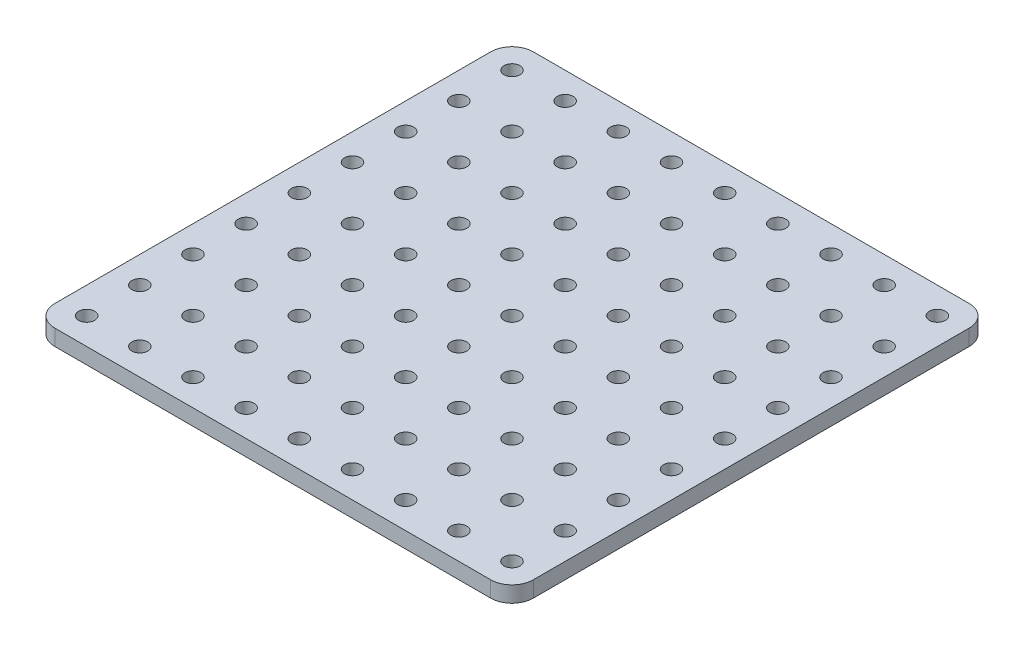
SolidWorks part; units mm, degrees
material "Thornel Mat VMA"
ref_plane "前视基准面" through (0, 0, 0) normal (0, 0, 1) x (1, 0, 0)
ref_plane "上视基准面" through (0, 0, 0) normal (0, 1, 0) x (1, 0, 0)
ref_plane "右视基准面" through (0, 0, 0) normal (1, 0, 0) x (0, 0, -1)
other "Configuration Table"
sketch "草图1" plane through (0, 0, 0) normal (0, 1, 0) x (1, 0, 0)
  line L1 (-45, -45) -> (45, -45)
  line L2 (-45, -45) -> (-45, 45)
  line L3 (-45, 45) -> (45, 45)
  line L4 (45, -45) -> (45, 45)
  line L5 (0, 45) -> (0, -45) construction
  line L6 (-45, 0) -> (45, 0) construction
  point P0 (0, 0)
  dimension "D1" = 90
  dimension "D2" = 90
extrude "凸台-拉伸1" add sketch "草图1" along normal blind 3
sketch "草图2" plane through (0, 3, 0) normal (0, 1, 0) x (1, 0, 0)
  circle A0 centre (-40, 40) radius 1.5
  circle A1 centre (40, 40) radius 1.5
  circle A2 centre (40, -40) radius 1.5
  circle A3 centre (-40, -40) radius 1.5
  point P12 (0, 0)
  dimension "D1" = 40
  dimension "D2" = 40
  dimension "D3" = 3
  dimension "D4" = 4
extrude "切除-拉伸1" cut sketch "草图2" against normal through all
sketch "草图3" plane through (0, 3, 0) normal (0, 1, 0) x (1, 0, 0)
  circle A1 centre (0, 0) radius 1.5
  circle A2 centre (10, 0) radius 1.5
  circle A3 centre (20, 0) radius 1.5
  circle A4 centre (30, 0) radius 1.5
  circle A5 centre (40, 0) radius 1.5
  circle A6 centre (10, 10) radius 1.5
  circle A7 centre (20, 10) radius 1.5
  circle A8 centre (30, 10) radius 1.5
  circle A9 centre (40, 10) radius 1.5
  circle A10 centre (10, 20) radius 1.5
  circle A11 centre (20, 20) radius 1.5
  circle A12 centre (30, 20) radius 1.5
  circle A13 centre (40, 20) radius 1.5
  circle A14 centre (10, 30) radius 1.5
  circle A15 centre (20, 30) radius 1.5
  circle A16 centre (30, 30) radius 1.5
  circle A17 centre (40, 30) radius 1.5
  circle A18 centre (10, 40) radius 1.5
  circle A19 centre (20, 40) radius 1.5
  circle A20 centre (30, 40) radius 1.5
  circle A21 centre (40, 40) radius 1.5
  circle A22 centre (0, 10) radius 1.5
  circle A23 centre (0, 20) radius 1.5
  circle A24 centre (0, 30) radius 1.5
  circle A25 centre (0, 40) radius 1.5
  circle A26 centre (-10, 0) radius 1.5
  circle A27 centre (-20, 0) radius 1.5
  circle A28 centre (-30, 0) radius 1.5
  circle A29 centre (-40, 0) radius 1.5
  circle A30 centre (-10, -10) radius 1.5
  circle A31 centre (-20, -10) radius 1.5
  circle A32 centre (-30, -10) radius 1.5
  circle A33 centre (-40, -10) radius 1.5
  circle A34 centre (-10, -20) radius 1.5
  circle A35 centre (-20, -20) radius 1.5
  circle A36 centre (-30, -20) radius 1.5
  circle A37 centre (-40, -20) radius 1.5
  circle A38 centre (-10, -30) radius 1.5
  circle A39 centre (-20, -30) radius 1.5
  circle A40 centre (-30, -30) radius 1.5
  circle A41 centre (-40, -30) radius 1.5
  circle A42 centre (-10, -40) radius 1.5
  circle A43 centre (-20, -40) radius 1.5
  circle A44 centre (-30, -40) radius 1.5
  circle A45 centre (-40, -40) radius 1.5
  circle A46 centre (0, -10) radius 1.5
  circle A47 centre (0, -20) radius 1.5
  circle A48 centre (0, -30) radius 1.5
  circle A49 centre (0, -40) radius 1.5
  dimension "D1" = 3
  dimension "D2" = 5
  dimension "D3" = 5
  dimension "D4" = 5
  dimension "D5" = 5
extrude "切除-拉伸2" cut sketch "草图3" against normal through all
sketch "草图5" plane through (0, 3, 0) normal (0, 1, 0) x (1, 0, 0)
  circle A0 centre (0, 0) radius 1.5
  circle A1 centre (-10, 0) radius 1.5
  circle A2 centre (-20, 0) radius 1.5
  circle A3 centre (-30, 0) radius 1.5
  circle A4 centre (-40, 0) radius 1.5
  circle A5 centre (-10, 10) radius 1.5
  circle A6 centre (-20, 10) radius 1.5
  circle A7 centre (-30, 10) radius 1.5
  circle A8 centre (-40, 10) radius 1.5
  circle A9 centre (-10, 20) radius 1.5
  circle A10 centre (-20, 20) radius 1.5
  circle A11 centre (-30, 20) radius 1.5
  circle A12 centre (-40, 20) radius 1.5
  circle A13 centre (-10, 30) radius 1.5
  circle A14 centre (-20, 30) radius 1.5
  circle A15 centre (-30, 30) radius 1.5
  circle A16 centre (-40, 30) radius 1.5
  circle A17 centre (-10, 40) radius 1.5
  circle A18 centre (-20, 40) radius 1.5
  circle A19 centre (-30, 40) radius 1.5
  circle A20 centre (-40, 40) radius 1.5
  circle A21 centre (0, 10) radius 1.5
  circle A22 centre (0, 20) radius 1.5
  circle A23 centre (0, 30) radius 1.5
  circle A24 centre (0, 40) radius 1.5
  circle A25 centre (10, 0) radius 1.5
  circle A26 centre (20, 0) radius 1.5
  circle A27 centre (30, 0) radius 1.5
  circle A28 centre (40, 0) radius 1.5
  circle A29 centre (10, -10) radius 1.5
  circle A30 centre (20, -10) radius 1.5
  circle A31 centre (30, -10) radius 1.5
  circle A32 centre (40, -10) radius 1.5
  circle A33 centre (10, -20) radius 1.5
  circle A34 centre (20, -20) radius 1.5
  circle A35 centre (30, -20) radius 1.5
  circle A36 centre (40, -20) radius 1.5
  circle A37 centre (10, -30) radius 1.5
  circle A38 centre (20, -30) radius 1.5
  circle A39 centre (30, -30) radius 1.5
  circle A40 centre (40, -30) radius 1.5
  circle A41 centre (10, -40) radius 1.5
  circle A42 centre (20, -40) radius 1.5
  circle A43 centre (30, -40) radius 1.5
  circle A44 centre (40, -40) radius 1.5
  circle A45 centre (0, -10) radius 1.5
  circle A46 centre (0, -20) radius 1.5
  circle A47 centre (0, -30) radius 1.5
  circle A48 centre (0, -40) radius 1.5
  dimension "D1" = 5
  dimension "D2" = 5
  dimension "D3" = 5
  dimension "D4" = 5
extrude "切除-拉伸3" cut sketch "草图5" against normal through all
fillet "圆角1" radius 4 4 edges at (-45, 1.5, 45) (45, 1.5, 45) (45, 1.5, -45) (-45, 1.5, -45)
